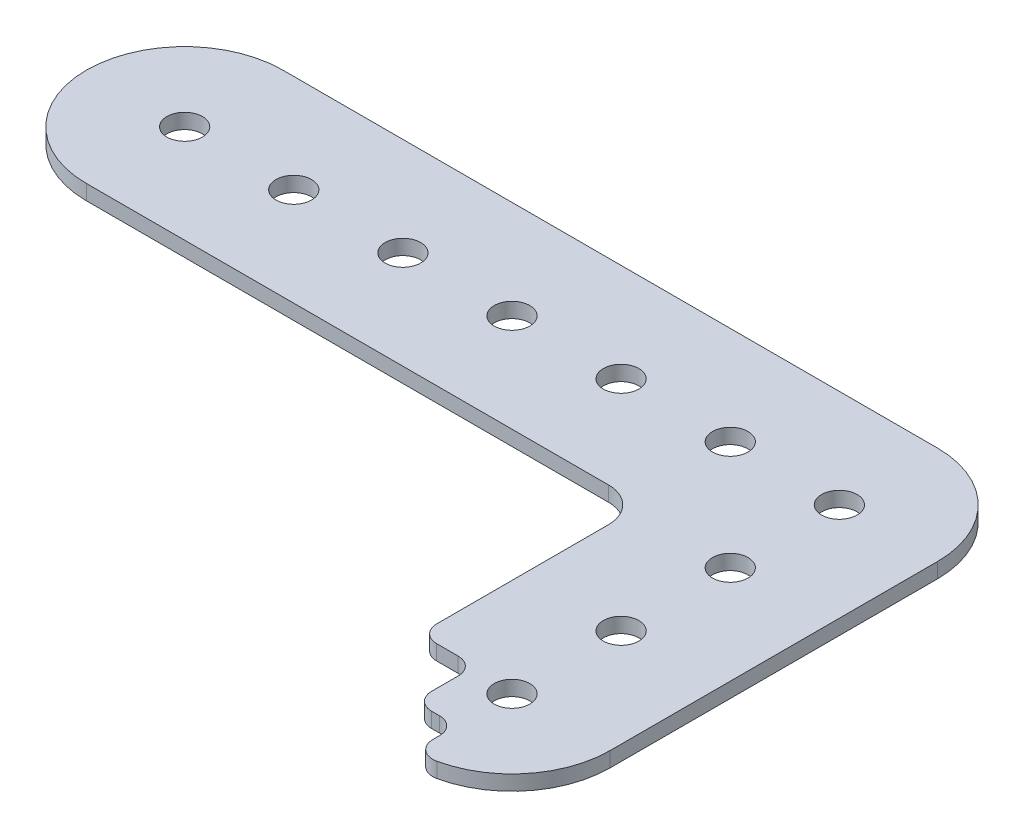
SolidWorks part; units mm, degrees
ref_plane "Front Plane" through (0, 0, 0) normal (0, 0, 1) x (1, 0, 0)
ref_plane "Top Plane" through (0, 0, 0) normal (0, 1, 0) x (1, 0, 0)
ref_plane "Right Plane" through (0, 0, 0) normal (1, 0, 0) x (0, 0, -1)
sketch "Sketch1" plane through (0, 0, 0) normal (0, 1, 0) x (1, 0, 0)
  line L0 (0, 0) -> (0, -50.8) construction
  line L1 (0, 0) -> (-78.27, 0) construction
  line L2 (-76.2, 11.43) -> (0, 11.43)
  line L3 (-76.2, -11.43) -> (0, -11.43)
  line L4 (-11.43, -38.1) -> (-11.43, -11.43)
  line L5 (11.43, -38.1) -> (11.43, 0)
  line L6 (-78.27, 0) -> (-76.2, 0) construction
  line L7 (-76.2, 0) -> (-63.5, 0) construction
  circle A0 centre (0, 0) radius 2.07
  circle A1 centre (-12.7, 0) radius 2.07
  circle A2 centre (-25.4, 0) radius 2.07
  circle A3 centre (-38.1, 0) radius 2.07
  circle A4 centre (-50.8, 0) radius 2.07
  circle A5 centre (-63.5, 0) radius 2.07
  circle A6 centre (-76.2, 0) radius 2.07
  circle A8 centre (0, -12.7) radius 2.07
  circle A9 centre (0, -25.4) radius 2.07
  circle A10 centre (0, -38.1) radius 2.07
  circle A12 centre (-76.2, 0) radius 11.43
  circle A13 centre (0, 0) radius 11.43
  circle A14 centre (0, -38.1) radius 11.43
  circle A15 centre (0, -50.8) radius 2.07 [skipped]
  circle A16 centre (-88.9, 0) radius 2.07 [skipped]
  point P18 (-82.757, 0)
  point P19 (-75.3567, 0)
  point P27 (-77.0746, 0)
  point P43 (-88.9, 0)
  point P44 (0, 0)
  dimension "D3" = 4.14
  dimension "D8" = 22.86
  dimension "D1" = 50.8
  dimension "D2" = 63.5
  dimension "D5" = 12.7
  dimension "D7" = 12.7
  dimension "D4" = 8
  dimension "D6" = 5
extrude "Boss-Extrude1" add sketch "Sketch1" along normal mid plane 1.75
fillet "Fillet1" radius 4 1 edges at (-11.43, 0, 11.43)
sketch "Sketch4" plane through (0, 0.875, 0) normal (0, 1, 0) x (1, 0, 0)
  line L0 (-4.93, -37.43) -> (-4.93, -48.4121)
  line L1 (-4.93, -37.43) -> (-11.43, -37.43)
  line L2 (-11.43, -38.1) -> (-11.43, -15.43) construction
  line L3 (-11.43, -38.1) -> (-11.43, -37.43)
  line L4 (-11.43, -37.43) -> (-11.43, -15.43) construction
  arc A0 (-11.43, -38.1) -> (11.43, -38.1) centre (0, -38.1) ccw construction
  arc A1 (-11.43, -38.1) -> (-4.93, -48.4121) centre (0, -38.1) ccw
  arc A2 (-4.93, -48.4121) -> (11.43, -38.1) centre (0, -38.1) ccw construction
  dimension "D1" = 6.5
  dimension "D2" = 22
extrude "Cut-Extrude3" cut sketch "Sketch4" against normal through all both and the other way through all
sketch "Sketch5" plane through (0, 0.875, 0) normal (0, 1, 0) x (1, 0, 0)
  line L0 (-4.93, -44.53) -> (0, -44.53)
  line L1 (-4.93, -48.4121) -> (-4.93, -37.43) construction
  line L2 (0, -44.53) -> (0, -49.53)
  line L3 (-4.93, -48.4121) -> (-4.93, -44.53)
  line L4 (-4.93, -44.53) -> (-4.93, -37.43) construction
  arc A0 (-4.93, -48.4121) -> (11.43, -38.1) centre (0, -38.1) ccw construction
  arc A1 (-4.93, -48.4121) -> (0, -49.53) centre (0, -38.1) ccw
  arc A2 (0, -49.53) -> (11.43, -38.1) centre (0, -38.1) ccw construction
  dimension "D1" = 5
extrude "Cut-Extrude4" cut sketch "Sketch5" against normal through all both and the other way through all
fillet "Fillet3" radius 2 5 edges at (0, 0, 44.53) (-4.93, 0, 44.53) (-4.93, 0, 37.43) (-11.43, 0, 37.43)
